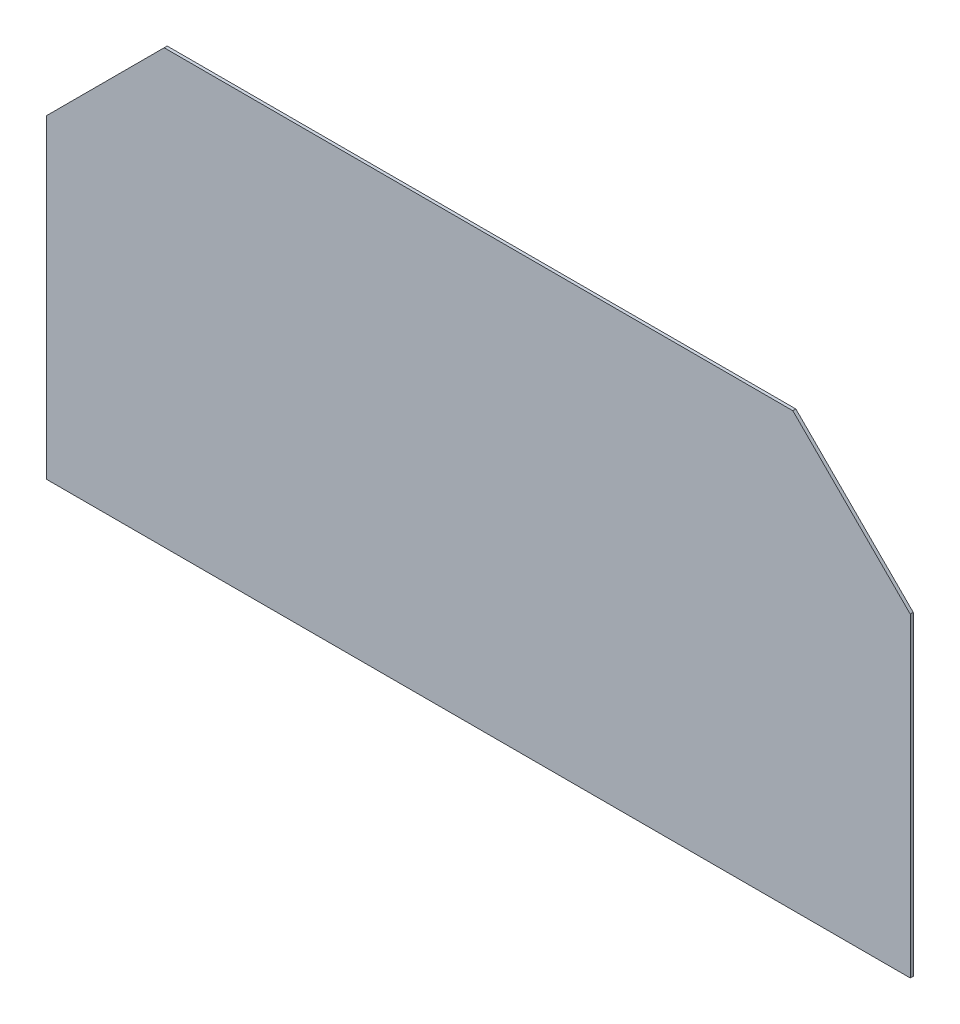
SolidWorks part; units mm, degrees
material "Solar cell"
ref_plane "Front Plane" through (0, 0, 0) normal (0, 0, 1) x (1, 0, 0)
ref_plane "Top Plane" through (0, 0, 0) normal (0, 1, 0) x (1, 0, 0)
ref_plane "Right Plane" through (0, 0, 0) normal (1, 0, 0) x (0, 0, -1)
sketch "Sketch1" plane through (0, 0, 0) normal (0, 0, 1) x (1, 0, 0)
  line L1 (-26.464, 26.4177) -> (53.686, 26.4177)
  line L2 (-26.464, 26.4177) -> (-26.464, -13.7323)
  line L3 (-26.464, -13.7323) -> (53.686, -13.7323)
  line L4 (53.686, 26.4177) -> (53.686, -13.7323)
  dimension "D1" = 40.15
  dimension "D2" = 80.15
extrude "Boss-Extrude2" add sketch "Sketch1" along normal blind 0.28 contours L1 L4 L3 L2
sketch "Sketch3" plane through (0, 0, 0.28) normal (0, 0, 1) x (1, 0, 0)
  line L0 (53.686, 26.4177) -> (53.686, 15.5177)
  line L1 (53.686, 26.4177) -> (53.686, -13.7323) construction
  line L2 (53.686, 15.5177) -> (42.786, 26.4177)
  line L3 (-26.464, 26.4177) -> (53.686, 26.4177) construction
  line L4 (42.786, 26.4177) -> (53.686, 26.4177)
extrude "Cut-Extrude1" cut sketch "Sketch3" against normal blind 110.28
sketch "Sketch6" plane through (0, 0, 0.28) normal (0, 0, 1) x (1, 0, 0)
  line L0 (-26.464, 26.4177) -> (-26.464, 15.5177)
  line L1 (-26.464, 26.4177) -> (-26.464, -13.7323) construction
  line L2 (-26.464, 15.5177) -> (-15.564, 26.4177)
  line L3 (-26.464, 26.4177) -> (42.786, 26.4177) construction
  line L4 (-15.564, 26.4177) -> (-26.464, 26.4177)
extrude "Cut-Extrude2" cut sketch "Sketch6" against normal blind 10
